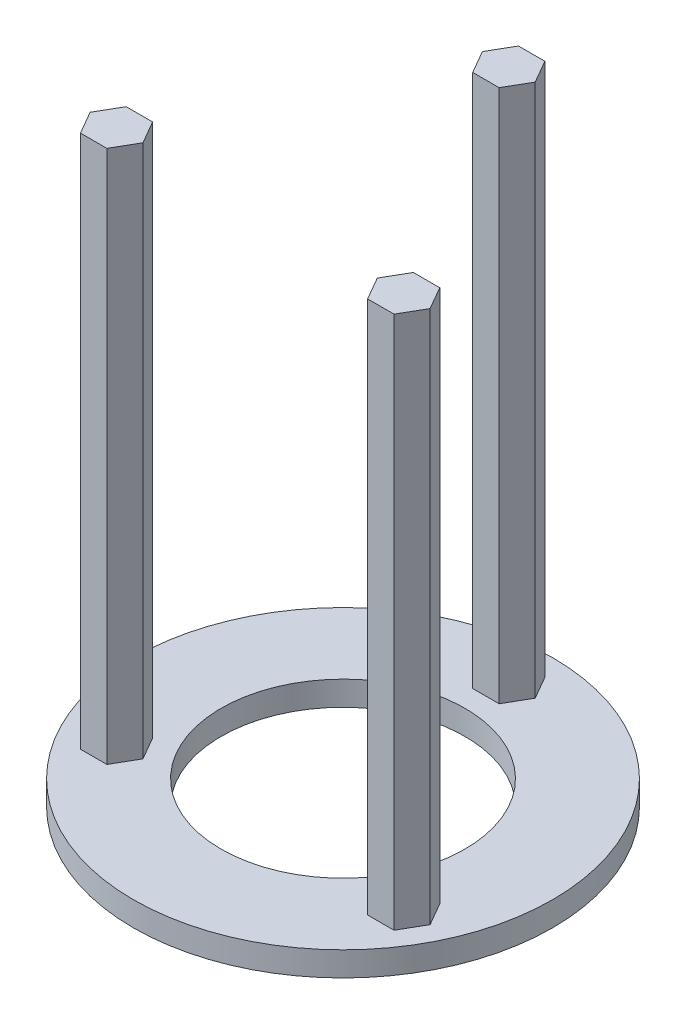
SolidWorks part; units mm, degrees
ref_plane "Спереди" through (0, 0, 0) normal (0, 0, 1) x (1, 0, 0)
ref_plane "Сверху" through (0, 0, 0) normal (0, 1, 0) x (1, 0, 0)
ref_plane "Справа" through (0, 0, 0) normal (1, 0, 0) x (0, 0, -1)
other "Configuration Table"
sketch "Эскиз1" plane through (0, 0, 0) normal (0, 1, 0) x (1, 0, 0)
  circle A0 centre (0, 0) radius 16
  circle A1 centre (0, 0) radius 27.5
  dimension "D1" = 55
extrude "Бобышка-Вытянуть1" add sketch "Эскиз1" along normal blind 3.2
sketch "Эскиз2" plane through (0, 3.2, 0) normal (0, 1, 0) x (1, 0, 0)
  line L0 (0, 16) -> (0, 27.5) construction
  line L1 (17.104, -13.875) -> (20.5681, -13.875)
  line L2 (3.4641, 21.75) -> (1.7321, 24.75)
  line L3 (1.7321, 24.75) -> (-1.7321, 24.75)
  line L4 (-1.7321, 24.75) -> (-3.4641, 21.75)
  line L5 (-3.4641, 21.75) -> (-1.7321, 18.75)
  line L6 (-1.7321, 18.75) -> (1.7321, 18.75)
  line L7 (1.7321, 18.75) -> (3.4641, 21.75)
  line L8 (20.5681, -13.875) -> (22.3002, -10.875)
  line L9 (22.3002, -10.875) -> (20.5681, -7.875)
  line L10 (20.5681, -7.875) -> (17.104, -7.875)
  line L11 (17.104, -7.875) -> (15.372, -10.875)
  line L12 (15.372, -10.875) -> (17.104, -13.875)
  line L13 (-20.5681, -7.875) -> (-22.3002, -10.875)
  line L14 (-22.3002, -10.875) -> (-20.5681, -13.875)
  line L15 (-20.5681, -13.875) -> (-17.104, -13.875)
  line L16 (-17.104, -13.875) -> (-15.372, -10.875)
  line L17 (-15.372, -10.875) -> (-17.104, -7.875)
  line L18 (-17.104, -7.875) -> (-20.5681, -7.875)
  circle A0 centre (0, 0) radius 16 construction
  circle A1 centre (0, 0) radius 27.5 construction
  circle A2 centre (0, 21.75) radius 3 construction
  point P30 (0, 0)
  dimension "D1" = 3
extrude "Бобышка-Вытянуть2" add sketch "Эскиз2" along normal blind 70
